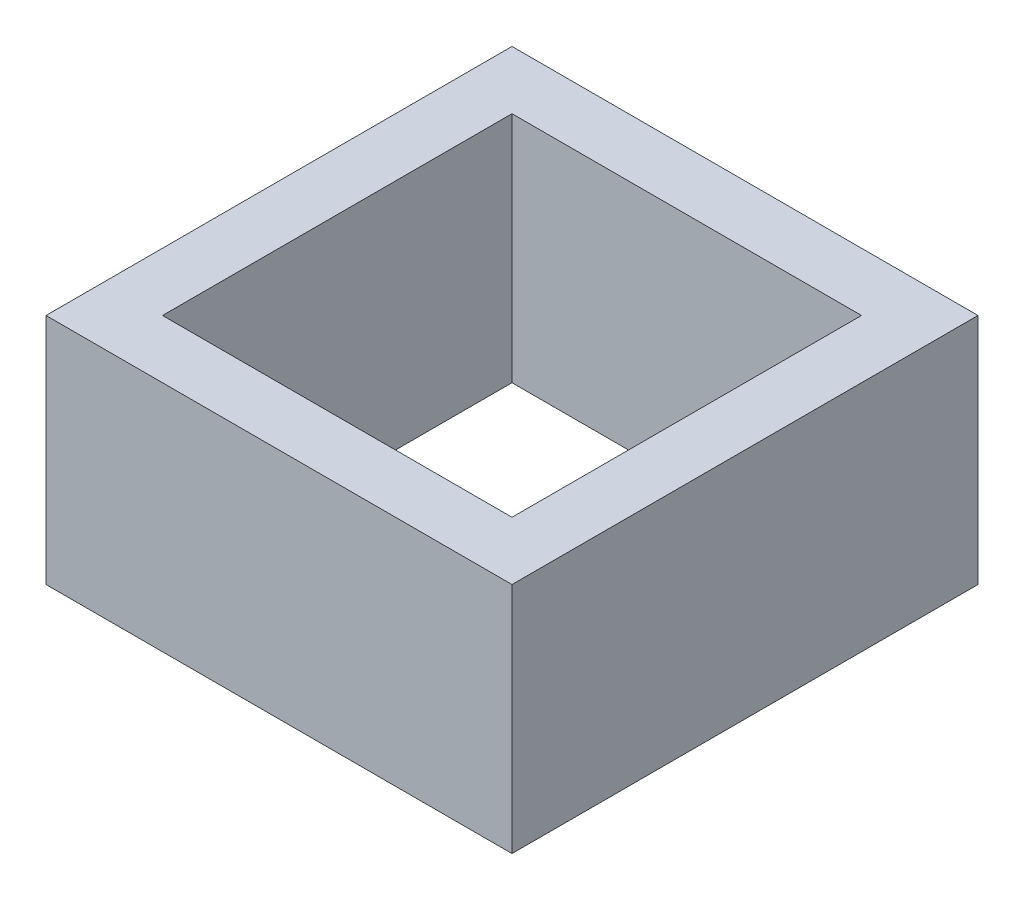
SolidWorks part; units mm, degrees
material "1060 Alloy"
ref_plane "Front Plane" through (0, 0, 0) normal (0, 0, 1) x (1, 0, 0)
ref_plane "Top Plane" through (0, 0, 0) normal (0, 1, 0) x (1, 0, 0)
ref_plane "Right Plane" through (0, 0, 0) normal (1, 0, 0) x (0, 0, -1)
sketch "Sketch1" plane through (0, 0, 0) normal (0, 1, 0) x (1, 0, 0)
  line L1 (-12.7, -12.7) -> (12.7, -12.7)
  line L2 (-12.7, -12.7) -> (-12.7, 12.7)
  line L3 (-12.7, 12.7) -> (12.7, 12.7)
  line L4 (12.7, -12.7) -> (12.7, 12.7)
  line L5 (-12.7, -12.7) -> (12.7, 12.7) construction
  line L6 (-12.7, 12.7) -> (12.7, -12.7) construction
  point P0 (0, 0)
  dimension "D1" = 25.4
extrude "Extrude-Thin1" add sketch "Sketch1" along normal blind 12.7 thin thin type one direction reverse wall 3.175
